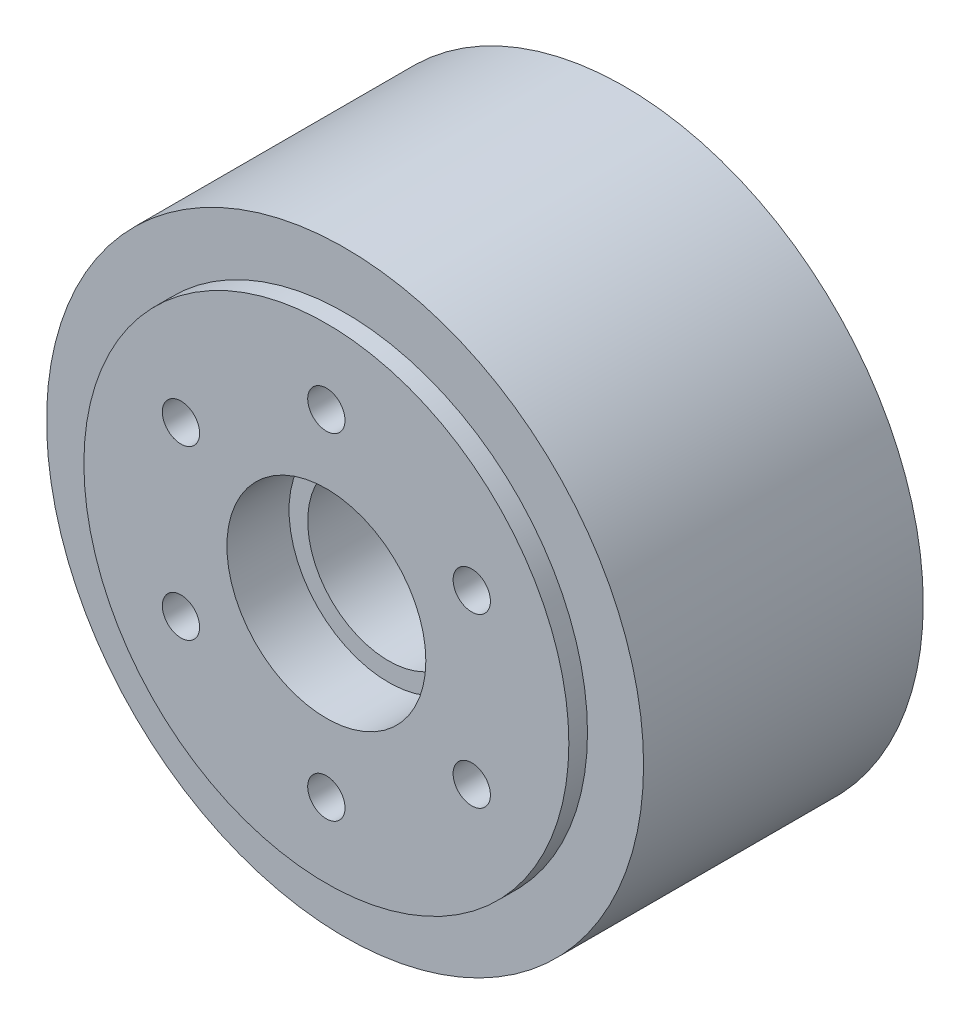
SolidWorks part; units mm, degrees
ref_plane "Front Plane" through (0, 0, 0) normal (0, 0, 1) x (1, 0, 0)
ref_plane "Top Plane" through (0, 0, 0) normal (0, 1, 0) x (1, 0, 0)
ref_plane "Right Plane" through (0, 0, 0) normal (1, 0, 0) x (0, 0, -1)
sketch "Sketch1" plane through (0, 0, 0) normal (1, 0, 0) x (0, 0, -1)
  line L0 (0, 0) -> (96.6686, 0) construction
  line L1 (0, 16) -> (0, 39)
  line L2 (0, 39) -> (3, 39)
  line L3 (3, 39) -> (3, 36)
  line L4 (3, 36) -> (48, 36)
  line L5 (48, 36) -> (48, 16)
  line L6 (48, 16) -> (38, 16)
  line L7 (38, 16) -> (38, 13)
  line L9 (10, 13) -> (10, 16)
  line L10 (10, 16) -> (0, 16)
  line L11 (3, 48) -> (48, 48) construction
  line L12 (10, 13) -> (38, 13)
  line L13 (0, 30) -> (48, 30) construction
  line L14 (0, 24) -> (48, 24) construction
  dimension "D1" = 48
  dimension "D2" = 3
  dimension "D3" = 3
  dimension "D4" = 12
  dimension "D5" = 16
  dimension "D6" = 10
  dimension "D7" = 45
  dimension "D8" = 3
  dimension "D9" = 6
  dimension "D10" = 24
revolve "Revolve1" add sketch "Sketch1" angle 360 about L0
sketch "Sketch2" plane through (0, 0, 0) normal (1, 0, 0) x (0, 0, -1)
  line L0 (47.99, 36.01) -> (3.01, 36.01)
  line L1 (3.01, 36.01) -> (3.01, 48.01)
  line L2 (3.01, 48.01) -> (47.99, 48.01)
  line L3 (47.99, 48.01) -> (47.99, 36.01)
  line L4 (0, 0) -> (48, 0) construction
  line L5 (48, -36) -> (48, 36) construction
  line L6 (48, 36) -> (3, 36) construction
  line L7 (3, -39) -> (3, 39) construction
  dimension "D1" = 12
  dimension "D2" = 0.01
  dimension "D3" = 0.01
  dimension "D4" = 0.01
revolve "Revolve2" add sketch "Sketch2" angle 360 about L4
sketch "Sketch3" plane through (0, 0, 0) normal (0, 0, 1) x (1, 0, 0)
  line L0 (0, 27) -> (0, 0) construction
  circle A0 centre (0, 27) radius 3
  circle A1 centre (23.3827, 13.5) radius 3
  circle A2 centre (23.3827, -13.5) radius 3
  circle A3 centre (0, -27) radius 3
  circle A4 centre (-23.3827, -13.5) radius 3
  circle A5 centre (-23.3827, 13.5) radius 3
  point P2 (0, 0)
  point P5 (20.7846, 12)
  point P16 (0, 0)
  dimension "D2" = 6
  dimension "D1" = 27
  dimension "D3" = 6
extrude "Cut-Extrude1" cut sketch "Sketch3" against normal through all
